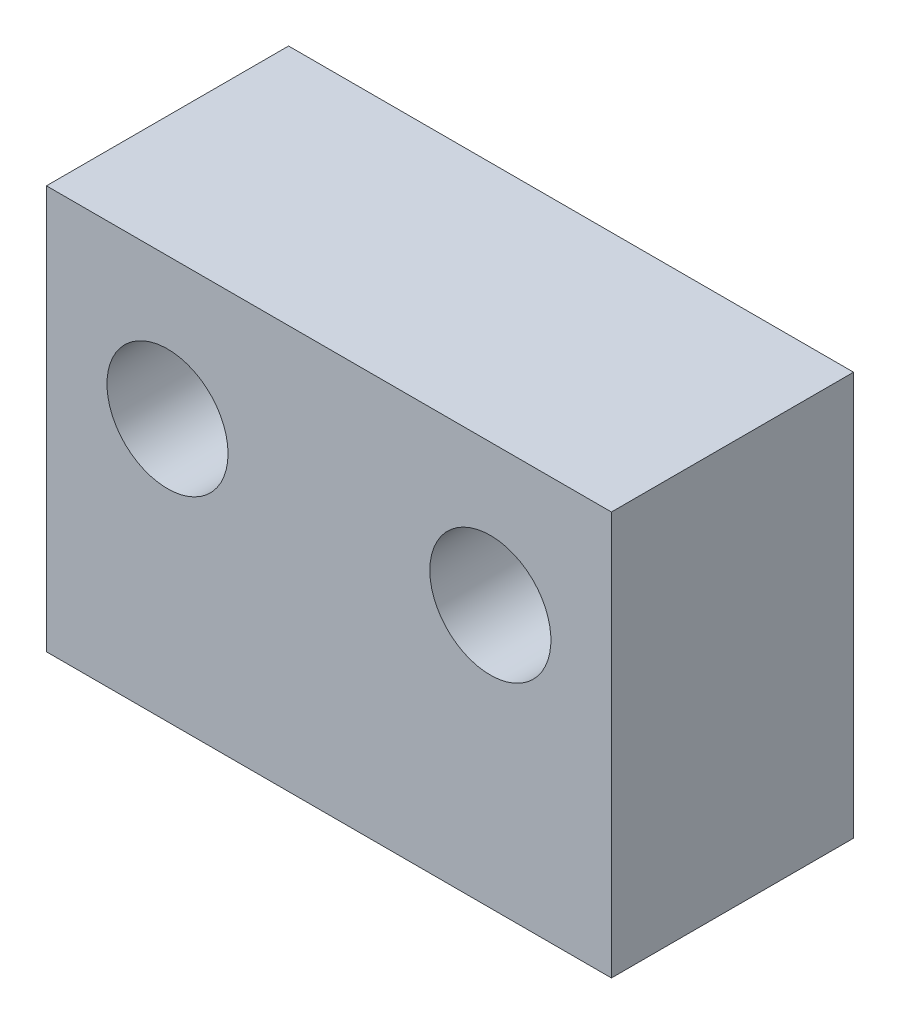
SolidWorks part; units mm, degrees
material "POM 乙缩醛共聚物"
ref_plane "前视基准面" through (0, 0, 0) normal (0, 0, 1) x (1, 0, 0)
ref_plane "上视基准面" through (0, 0, 0) normal (0, 1, 0) x (1, 0, 0)
ref_plane "右视基准面" through (0, 0, 0) normal (1, 0, 0) x (0, 0, -1)
sketch "草图1" plane through (0, 0, 0) normal (0, 0, 1) x (1, 0, 0)
  line L1 (-7, 5) -> (7, 5)
  line L2 (-7, 5) -> (-7, -5)
  line L3 (-7, -5) -> (7, -5)
  line L4 (7, 5) -> (7, -5)
  line L5 (-7, 5) -> (7, -5) construction
  line L6 (-7, -5) -> (7, 5) construction
  point P0 (0, 0)
  dimension "D1" = 10
  dimension "D2" = 14
extrude "凸台-拉伸1" add sketch "草图1" along normal blind 6
sketch "草图3" plane through (0, 0, 6) normal (0, 0, 1) x (1, 0, 0)
  line L0 (-7, 1.5) -> (7, 1.5) construction
  line L1 (-7, 5) -> (-7, -5) construction
  line L2 (7, -5) -> (7, 5) construction
  line L3 (-7, -5) -> (7, -5) construction
  line L4 (0, 5) -> (0, 1.5) construction
  line L5 (7, 5) -> (-7, 5) construction
  circle A0 centre (-4, 1.5) radius 1.5
  circle A1 centre (4, 1.5) radius 1.5
  dimension "D2" = 4
  dimension "D3" = 3
  dimension "D1" = 6.5
extrude "切除-拉伸1" cut sketch "草图3" against normal through all
